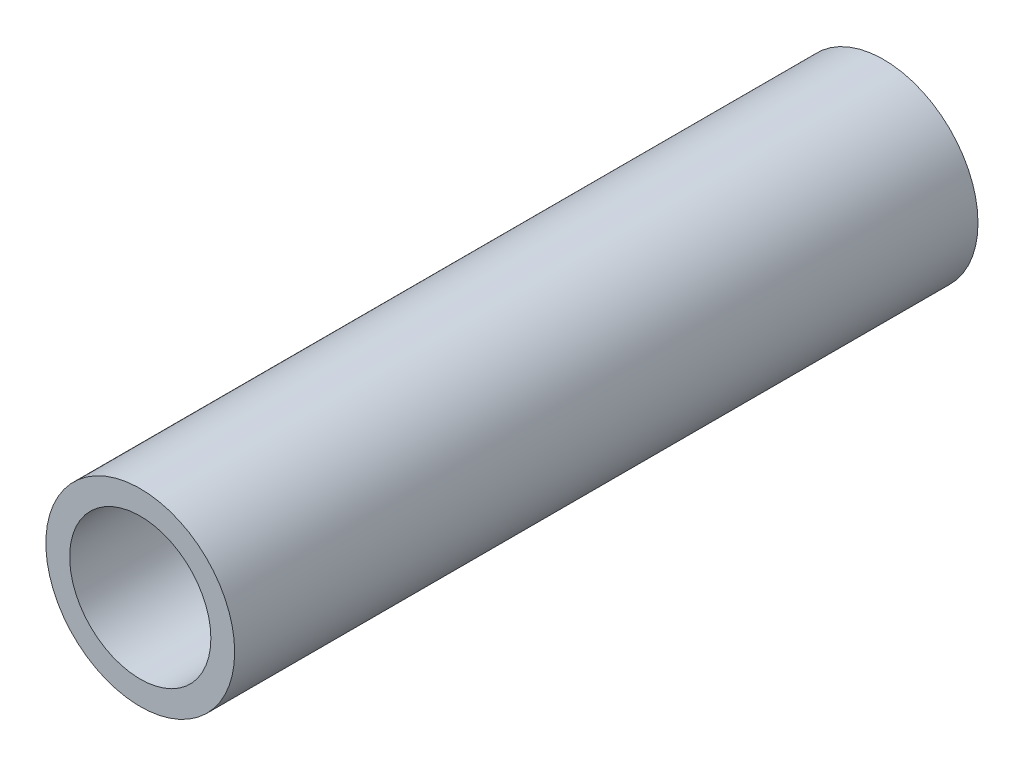
SolidWorks part; units mm, degrees
ref_plane "Alzado" through (0, 0, 0) normal (0, 0, 1) x (1, 0, 0)
ref_plane "Planta" through (0, 0, 0) normal (0, 1, 0) x (1, 0, 0)
ref_plane "Vista lateral" through (0, 0, 0) normal (1, 0, 0) x (0, 0, -1)
sketch "Croquis1" plane through (0, 0, 0) normal (0, 0, 1) x (1, 0, 0)
  circle A0 centre (0, 0) radius 12.7
  circle A1 centre (0, 0) radius 9.5
  dimension "D1" = 25.4
  dimension "D2" = 3.2
extrude "Saliente-Extruir1" add sketch "Croquis1" along normal mid plane 100
